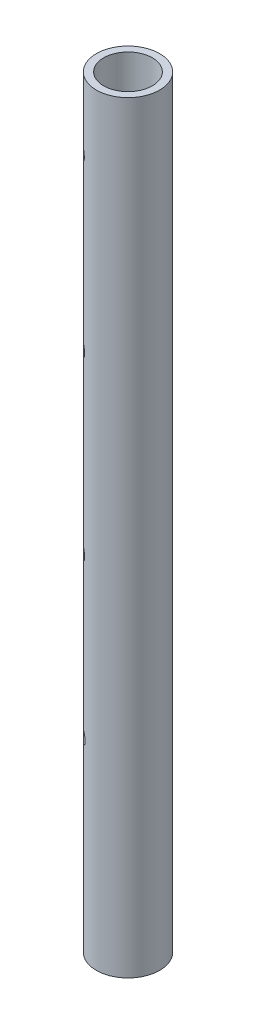
SolidWorks part; units mm, degrees
material "PVC 0.007 Plasticized"
ref_plane "Front Plane" through (0, 0, 0) normal (0, 0, 1) x (1, 0, 0)
ref_plane "Top Plane" through (0, 0, 0) normal (0, 1, 0) x (1, 0, 0)
ref_plane "Right Plane" through (0, 0, 0) normal (1, 0, 0) x (0, 0, -1)
sketch "Sketch2" plane through (0, 0, 0) normal (0, 1, 0) x (1, 0, 0)
  circle A0 centre (0, 0) radius 16.51
  dimension "D1" = 33.02
extrude "Boss-Extrude1" add sketch "Sketch2" along normal blind 398.018
sketch "Sketch3" plane through (0, 0, 0) normal (0, -1, 0) x (1, 0, 0)
  circle A0 centre (0, 0) radius 12.7
extrude "Cut-Extrude1" cut sketch "Sketch3" against normal blind 398.018
hole_wizard "A (0.234) Diameter Hole1" positions "3DSketch6" profile "Sketch8" hole size "A" standard "ANSI Inch"
sketch3d "3DSketch6"
  point P0 (-11.2297, 361.6581, 12.1026)
  point P2 (-10.7687, 273.3893, 12.5146)
  point P4 (-10.7687, 181.417, 12.5146)
  point P6 (-10.2913, 98.7036, 12.9101)
sketch "Sketch8" plane through (-11.2297, 361.6581, 12.1026) normal (0, 1, 0) x (0.733, 0, 0.6802)
  line L0 (0, 0) -> (0, 3.81)
  line L1 (0, 3.81) -> (2.9718, 3.81)
  line L2 (2.9718, 3.81) -> (2.9718, 0)
  line L5 (2.9718, 0) -> (0, 0)
  line L11 (0, -6.35) -> (0, 107.95) construction
  dimension "Thru Hole Dia." = 5.9436
  dimension "Thru Hole Depth" = 3.81
hole_wizard "N (0.302) Diameter Hole1" positions "3DSketch10" profile "Sketch9" hole size "N" standard "ANSI Inch"
sketch3d "3DSketch10"
  point P0 (-5.4178, 40.2008, -15.5958)
sketch "Sketch9" plane through (-5.4178, 40.2008, -15.5958) normal (0, 1, 0) x (-0.9446, 0, 0.3282)
  line L0 (0, 0) -> (0, 3.81)
  line L1 (0, 3.81) -> (3.81, 3.81)
  line L2 (3.81, 3.81) -> (3.81, 0)
  line L5 (3.81, 0) -> (0, 0)
  line L11 (0, -6.35) -> (0, 107.95) construction
  dimension "Thru Hole Dia." = 7.62
  dimension "Thru Hole Depth" = 3.81
